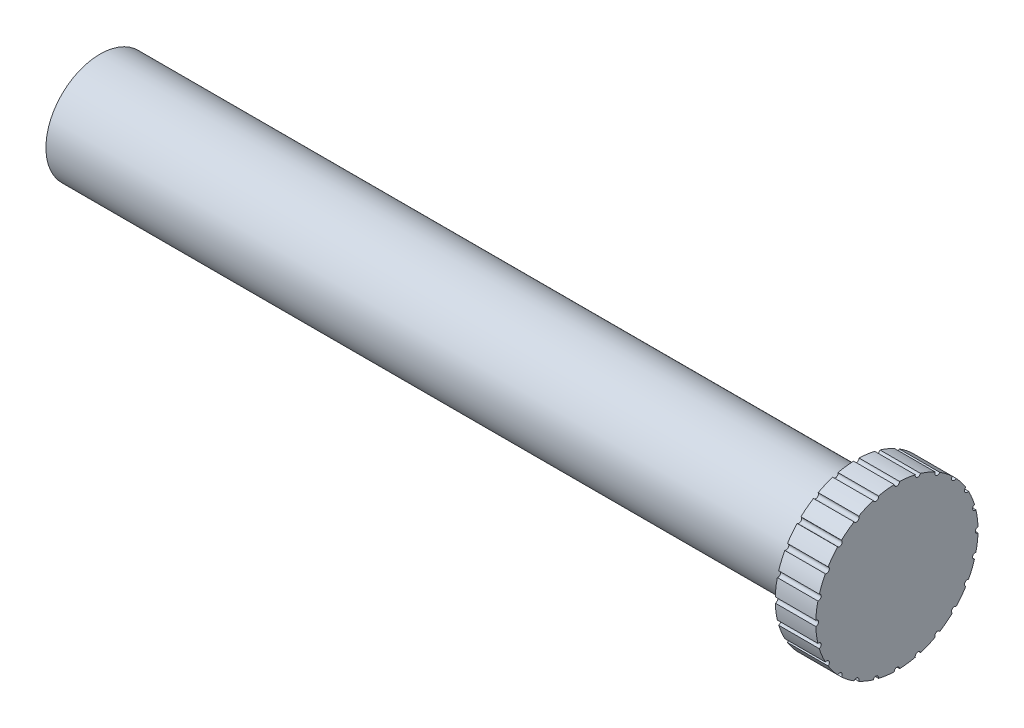
SolidWorks part; units mm, degrees
ref_plane "Front Plane" through (0, 0, 0) normal (0, 0, 1) x (1, 0, 0)
ref_plane "Top Plane" through (0, 0, 0) normal (0, 1, 0) x (1, 0, 0)
ref_plane "Right Plane" through (0, 0, 0) normal (1, 0, 0) x (0, 0, -1)
sketch "Sketch1" plane through (0, 0, 0) normal (1, 0, 0) x (0, 0, -1)
  circle A0 centre (0, 0) radius 4
  dimension "D1" = 8
extrude "Boss-Extrude1" add sketch "Sketch1" along normal blind 55.94
sketch "Sketch2" plane through (55.94, 0, 0) normal (1, 0, 0) x (0, 0, -1)
  circle A0 centre (0, 0) radius 6
  dimension "D1" = 12
extrude "Boss-Extrude2" add sketch "Sketch2" along normal blind 3
sketch "Sketch3" plane through (58.94, 0, 0) normal (1, 0, 0) x (0, 0, -1)
  circle A0 centre (0, 0) radius 6 construction
  circle A1 centre (0, 0) radius 6
  circle A2 centre (-6, 0) radius 0.2
  circle M3 centre (0, 0) radius 6
  dimension "D1" = 0.4
extrude "Cut-Extrude1" cut sketch "Sketch3" against normal up to next contours A2 M3 | A2 M3
pattern_circular "CirPattern1" count 25 every 15 about axis through (0, 0, 0) along (1, 0, 0) of "Cut-Extrude1"
